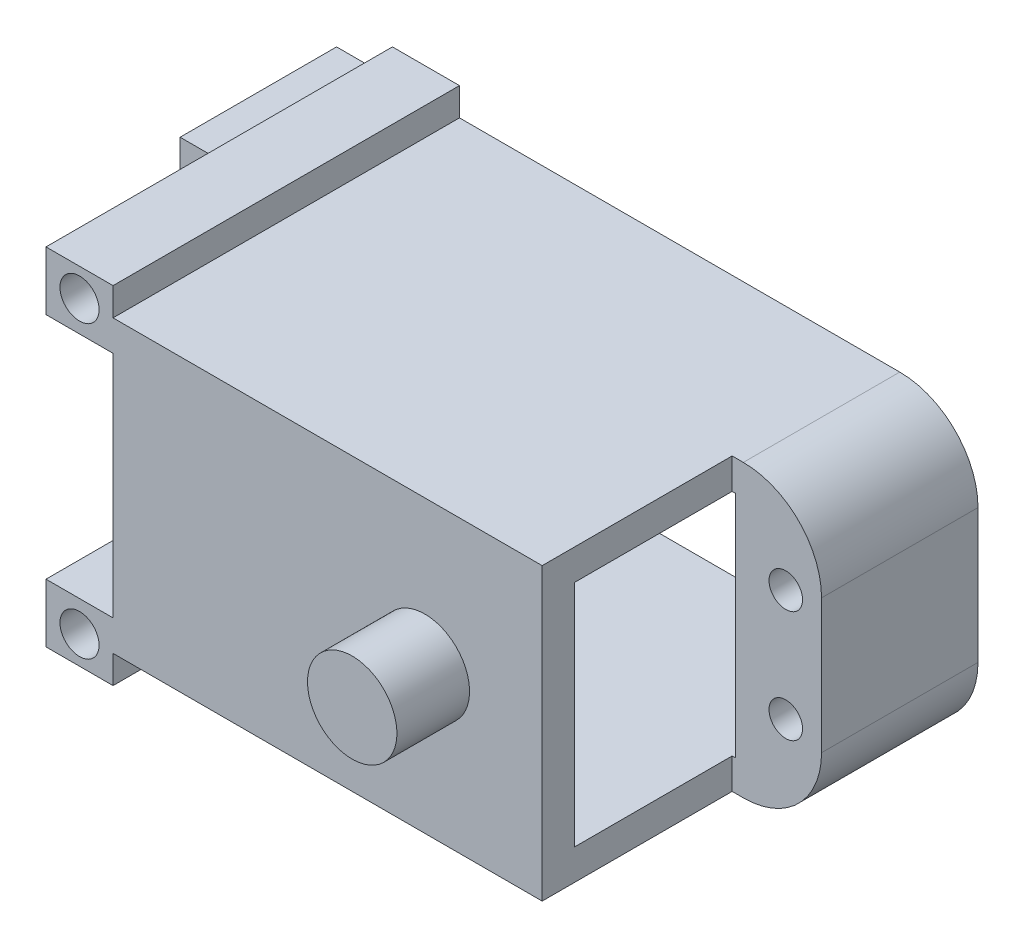
SolidWorks part; units mm, degrees
ref_plane "Спереди" through (0, 0, 0) normal (0, 0, 1) x (1, 0, 0)
ref_plane "Сверху" through (0, 0, 0) normal (0, 1, 0) x (1, 0, 0)
ref_plane "Справа" through (0, 0, 0) normal (1, 0, 0) x (0, 0, -1)
ref_plane "Плоскость4" through (0, 0, 12) normal (0, 0, 1) x (1, 0, 0)
sketch "Эскиз1" plane through (0, 0, 12) normal (0, 0, 1) x (1, 0, 0)
  line L0 (-28.7, 15.5) -> (-28.7, -13)
  line L1 (-28.7, -13) -> (28.7, -13)
  line L2 (28.7, -13) -> (28.7, 15.5)
  line L3 (28.7, 15.5) -> (-28.7, 15.5)
extrude "Бобышка-Вытянуть1" add sketch "Эскиз1" against normal blind 12
sketch "Эскиз2" plane through (0, 0, 12) normal (0, 0, 1) x (1, 0, 0)
  line L0 (28.7, 13) -> (28.7, -13)
  line L1 (28.7, -13) -> (-28.7, -13)
  line L2 (-28.7, -13) -> (-28.7, 13)
  line L3 (-28.7, 13) -> (28.7, 13)
extrude "Бобышка-Вытянуть2" add sketch "Эскиз2" along normal blind 19
sketch "Эскиз3" plane through (-28.7, 0, 0) normal (-1, 0, 0) x (0, 0, 1)
  line L0 (28.1, 10.25) -> (12, 10.25)
  line L1 (12, 10.25) -> (12, -10.25)
  line L2 (12, -10.25) -> (28.1, -10.25)
  line L3 (28.1, -10.25) -> (28.1, 10.25)
extrude "Вырез-Вытянуть1" cut sketch "Эскиз3" against normal blind 7.7
sketch "Эскиз4" plane through (-21, 0, 0) normal (-1, 0, 0) x (0, 0, 1)
  line L0 (0, -10.25) -> (28.1, -10.25)
  line L1 (28.1, -10.25) -> (28.1, 10.25)
  line L2 (28.1, 10.25) -> (0, 10.25)
  line L3 (0, 10.25) -> (0, -10.25)
extrude "Вырез-Вытянуть2" cut sketch "Эскиз4" against normal blind 41.7
sketch "Эскиз5" plane through (20.7, 0, 0) normal (-1, 0, 0) x (0, 0, 1)
  line L0 (0, -10.25) -> (31, -10.25)
  line L1 (31, -10.25) -> (31, 10.25)
  line L2 (31, 10.25) -> (0, 10.25)
  line L3 (0, 10.25) -> (0, -10.25)
extrude "Вырез-Вытянуть3" cut sketch "Эскиз5" against normal blind 0.3
sketch "Эскиз6" plane through (0, 0, 31) normal (0, 0, 1) x (1, 0, 0)
  line L0 (28.7, -13) -> (28.7, 13)
  line L1 (28.7, 13) -> (20.7, 13)
  line L2 (20.7, 13) -> (20.7, 10.25)
  line L3 (20.7, 10.25) -> (21, 10.25)
  line L4 (21, 10.25) -> (21, -10.25)
  line L5 (21, -10.25) -> (20.7, -10.25)
  line L6 (20.7, -10.25) -> (20.7, -13)
  line L7 (20.7, -13) -> (28.7, -13)
extrude "Вырез-Вытянуть4" cut sketch "Эскиз6" against normal blind 2.9
sketch "Эскиз7" plane through (28.7, 0, 0) normal (1, 0, 0) x (0, 0, -1)
  line L0 (-12, 13) -> (0, 13)
  line L1 (0, 13) -> (0, 15.5)
  line L2 (0, 15.5) -> (-12, 15.5)
  line L3 (-12, 15.5) -> (-12, 13)
extrude "Вырез-Вытянуть5" cut sketch "Эскиз7" against normal blind 46.4
sketch "Эскиз8" plane through (-28.7, 0, 0) normal (-1, 0, 0) x (0, 0, 1)
  line L0 (12, -13) -> (31, -13)
  line L1 (31, -13) -> (31, 13)
  line L2 (31, 13) -> (12, 13)
  line L3 (12, 13) -> (12, 10.25)
  line L4 (12, 10.25) -> (28.1, 10.25)
  line L5 (28.1, 10.25) -> (28.1, -10.25)
  line L6 (28.1, -10.25) -> (12, -10.25)
  line L7 (12, -10.25) -> (12, -13)
extrude "Вырез-Вытянуть6" cut sketch "Эскиз8" against normal blind 7.7
sketch "Эскиз9" plane through (0, 0, 28.1) normal (0, 0, 1) x (1, 0, 0)
  line L0 (28.7, -13) -> (28.7, 13)
  line L1 (28.7, 13) -> (20.7, 13)
  line L2 (20.7, 13) -> (20.7, 10.25)
  line L3 (20.7, 10.25) -> (21, 10.25)
  line L4 (21, 10.25) -> (21, -10.25)
  line L5 (21, -10.25) -> (20.7, -10.25)
  line L6 (20.7, -10.25) -> (20.7, -13)
  line L7 (20.7, -13) -> (28.7, -13)
extrude "Вырез-Вытянуть7" cut sketch "Эскиз9" against normal blind 14.1
sketch "Эскиз10" plane through (-21, 0, 0) normal (-1, 0, 0) x (0, 0, 1)
  line L0 (12, -13) -> (31, -13)
  line L1 (31, -13) -> (31, 13)
  line L2 (31, 13) -> (12, 13)
  line L3 (12, 13) -> (12, 10.25)
  line L4 (12, 10.25) -> (28.1, 10.25)
  line L5 (28.1, 10.25) -> (28.1, -10.25)
  line L6 (28.1, -10.25) -> (12, -10.25)
  line L7 (12, -10.25) -> (12, -13)
extrude "Вырез-Вытянуть8" cut sketch "Эскиз10" against normal blind 3.3
sketch "Эскиз11" plane through (0, -13, 0) normal (0, -1, 0) x (1, 0, 0)
  line L0 (-17.7, 0) -> (-28.7, 0)
  line L1 (-28.7, 0) -> (-28.7, 12)
  line L2 (-28.7, 12) -> (-17.7, 12)
  line L3 (-17.7, 12) -> (-17.7, 0)
extrude "Бобышка-Вытянуть3" add sketch "Эскиз11" along normal blind 2.5
sketch "Эскиз12" plane through (-17.7, 0, 0) normal (-1, 0, 0) x (0, 0, 1)
  line L0 (19, -13) -> (19, -10.25)
  line L1 (19, -10.25) -> (31, -10.25)
  line L2 (31, -10.25) -> (31, -13)
  line L3 (31, -13) -> (19, -13)
extrude "Бобышка-Вытянуть4" add sketch "Эскиз12" along normal blind 6
sketch "Эскиз13" plane through (0, -13, 0) normal (0, -1, 0) x (1, 0, 0)
  line L0 (-23.7, 31) -> (-17.7, 31)
  line L1 (-17.7, 31) -> (-17.7, 19)
  line L2 (-17.7, 19) -> (-23.7, 19)
  line L3 (-23.7, 19) -> (-23.7, 31)
extrude "Бобышка-Вытянуть5" add sketch "Эскиз13" along normal blind 2.5
sketch "Эскиз14" plane through (-17.7, 0, 0) normal (-1, 0, 0) x (0, 0, 1)
  line L0 (31, 15.5) -> (31, 10.25)
  line L1 (31, 10.25) -> (19, 10.25)
  line L2 (19, 10.25) -> (19, 15.5)
  line L3 (19, 15.5) -> (31, 15.5)
extrude "Бобышка-Вытянуть6" add sketch "Эскиз14" along normal blind 6
sketch "Эскиз15" plane through (0, 0, 0) normal (0, 0, -1) x (-1, 0, 0)
  line L0 (28.7, -15.5) -> (28.7, -13)
  line L1 (28.7, -13) -> (23.7, -13)
  line L2 (23.7, -13) -> (23.7, -15.5)
  line L3 (23.7, -15.5) -> (28.7, -15.5)
extrude "Вырез-Вытянуть9" cut sketch "Эскиз15" against normal through all
sketch "Эскиз16" plane through (0, 0, 0) normal (0, 0, -1) x (-1, 0, 0)
  line L0 (23.7, 15.5) -> (23.7, 13)
  line L1 (23.7, 13) -> (28.7, 13)
  line L2 (28.7, 13) -> (28.7, 15.5)
  line L3 (28.7, 15.5) -> (23.7, 15.5)
extrude "Вырез-Вытянуть10" cut sketch "Эскиз16" against normal through all
sketch "Эскиз17" plane through (0, 0, 12) normal (0, 0, 1) x (1, 0, 0)
  line L0 (-23.7, 13) -> (-23.7, -13)
  line L1 (-23.7, -13) -> (-28.7, -13)
  line L2 (-28.7, -13) -> (-28.7, 13)
  line L3 (-28.7, 13) -> (-23.7, 13)
extrude "Бобышка-Вытянуть7" add sketch "Эскиз17" along normal blind 2
ref_plane "Плоскость5" through (0, 0, 0) normal (0, -1, 0) x (1, 0, 0)
sketch "Эскиз19" plane through (0, 0, 0) normal (0, -1, 0) x (1, 0, 0)
  line L0 (14.2, 37.5) -> (10.2, 37.5)
  line L1 (10.2, 37.5) -> (10.2, 31)
  line L2 (10.2, 31) -> (14.2, 31)
  line L3 (14.2, 31) -> (14.2, 37.5)
  line L4 (10.2, 37.5) -> (10.2, 31) construction
revolve "Повернуть1" add sketch "Эскиз19" angle 360 about L4
hole_wizard "Диаметр отверстия Ø3.5 (3.5)1" positions "Эскиз21" profile "Эскиз20" hole size "Ø3.5" standard "Ansi Metric"
sketch "Эскиз21" plane through (0, 0, 31) normal (0, 0, 1) x (1, 0, 0)
  point P0 (-20.7, 13)
  point P1 (-20.7, -13)
sketch "Эскиз20" plane through (-20.7, 13, 31) normal (1, 0, 0) x (0, -1, 0)
  line L0 (0, 0) -> (0, 12)
  line L1 (0, 12) -> (1.75, 12)
  line L2 (1.75, 12) -> (1.75, 0)
  line L5 (1.75, 0) -> (0, 0)
  line L11 (0, -6.35) -> (0, 107.95) construction
  dimension "Диаметр сквозного отверстия" = 3.5
  dimension "Глубина сквозного отверстия" = 12
hole_wizard "Диаметр отверстия Ø3.0 (3)3" positions "Эскиз25" profile "Эскиз24" hole size "Ø3.0" standard "Ansi Metric"
sketch "Эскиз25" plane through (0, 0, 0) normal (0, 0, -1) x (-1, 0, 0)
  point P0 (-25.5, -5)
  point P1 (-25.5, 5)
  point P2 (25.5, -5)
  point P3 (25.5, 5)
sketch "Эскиз24" plane through (25.5, -5, 0) normal (1, 0, 0) x (0, 1, 0)
  line L0 (0, 0) -> (0, 37.5)
  line L1 (0, 37.5) -> (1.5, 37.5)
  line L2 (1.5, 37.5) -> (1.5, 0)
  line L5 (1.5, 0) -> (0, 0)
  line L11 (0, -6.35) -> (0, 107.95) construction
  dimension "Диаметр сквозного отверстия" = 3
  dimension "Глубина сквозного отверстия" = 37.5
hole_wizard "Диаметр отверстия Ø3.5 (3.5)3" positions "Эскиз27" profile "Эскиз26" hole size "Ø3.5" standard "Ansi Metric" end condition through all
sketch "Эскиз27" plane through (0, 0, 12) normal (0, 0, 1) x (1, 0, 0)
  point P0 (-20.7, 13)
  point P1 (-20.7, -13)
sketch "Эскиз26" plane through (-20.7, 13, 12) normal (1, 0, 0) x (0, -1, 0)
  line L0 (0, 0) -> (0, 12)
  line L1 (0, 12) -> (1.75, 12)
  line L2 (1.75, 12) -> (1.75, 0)
  line L5 (1.75, 0) -> (0, 0)
  line L11 (0, -6.35) -> (0, 107.95) construction
  dimension "Диаметр сквозного отверстия" = 3.5
  dimension "Глубина сквозного отверстия" = 12
fillet "Скругление1" radius 7 2 edges at (28.7, -13, 7) (28.7, 13, 7)
sketch "Эскиз28" plane through (0, 0, 31) normal (0, 0, 1) x (1, 0, 0)
  line L0 (-17.7, 0) -> (-21, 0) construction
  line L1 (-23.7, 15.5) -> (-17.7, 15.5)
  line L2 (-23.7, 15.5) -> (-23.7, 10.25)
  line L3 (-23.7, 10.25) -> (-17.7, 10.25)
  line L4 (-17.7, 15.5) -> (-17.7, 10.25)
  line L5 (-17.7, -10.25) -> (-17.7, 10.25) construction
  line L6 (-21, 10.25) -> (-21, -10.25) construction
  line L7 (-23.7, -10.25) -> (-17.7, -10.25)
  line L8 (-17.7, -15.5) -> (-17.7, -10.25)
  line L9 (-23.7, -15.5) -> (-17.7, -15.5)
  line L10 (-23.7, -15.5) -> (-23.7, -10.25)
  circle A0 centre (-20.7, 13) radius 1.75
  circle A1 centre (-20.7, -13) radius 1.75
extrude "Бобышка-Вытянуть8" add sketch "Эскиз28" against normal up to surface (7 mm away) from surface at -12 up to face at (-18.95, 13, 12) starting at face at (-18.95, -13, 19)
